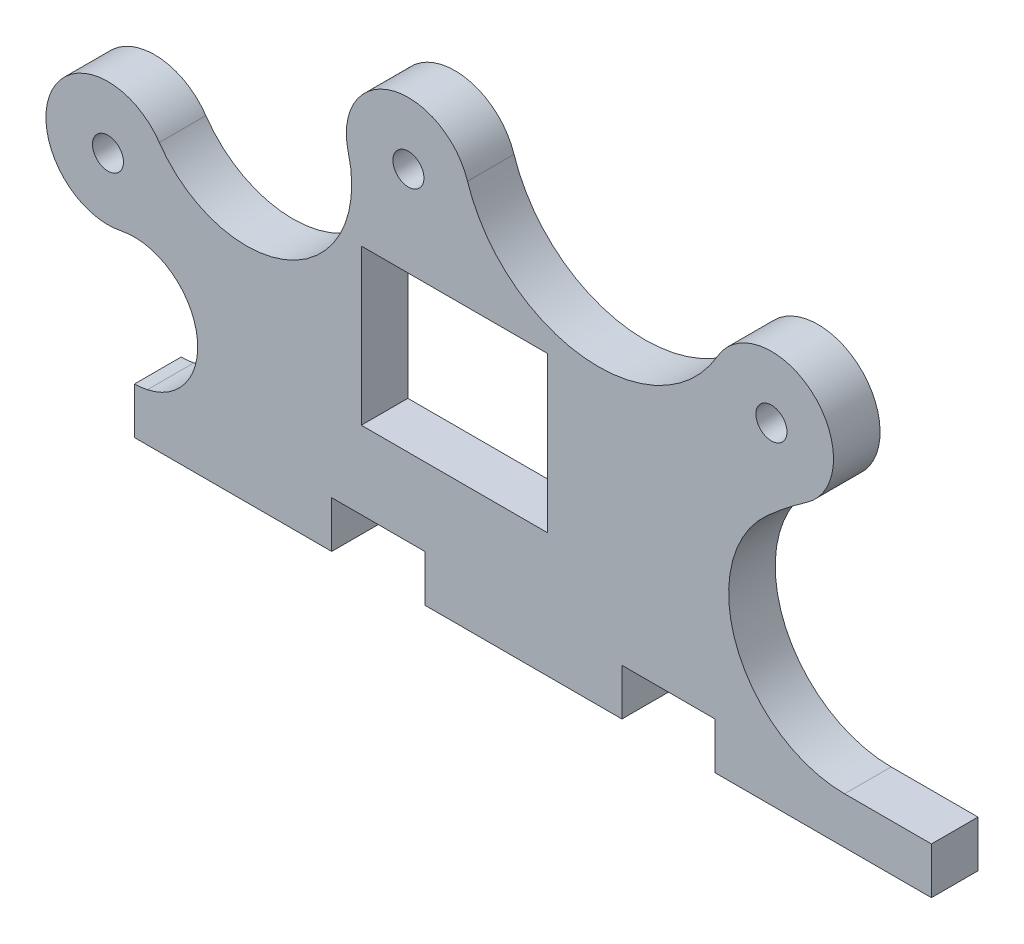
SolidWorks part; units mm, degrees
material "Acrylic (Medium-high impact)"
ref_plane "Front Plane" through (0, 0, 0) normal (0, 0, 1) x (1, 0, 0)
ref_plane "Top Plane" through (0, 0, 0) normal (0, 1, 0) x (1, 0, 0)
ref_plane "Right Plane" through (0, 0, 0) normal (1, 0, 0) x (0, 0, -1)
sketch "스케치2" plane through (0, 0, 0) normal (0, 0, 1) x (1, 0, 0)
  line L0 (-17.4812, 10.16) -> (-17.4856, 10.1652) construction
  line L1 (-17.4812, -10.16) -> (17.4812, -10.16) construction
  line L2 (-17.4812, -10.16) -> (-17.4812, 10.16) construction
  line L3 (-17.4812, 10.16) -> (17.4812, 10.16) construction
  line L4 (17.4812, -10.16) -> (17.4812, 10.16) construction
  line L5 (-17.4812, -10.16) -> (17.4812, 10.16) construction
  line L6 (-17.4812, 10.16) -> (17.4812, -10.16) construction
  line L7 (-17.4856, 10.1652) -> (-15.1875, 12.0936) construction
  line L8 (-15.1875, 12.0936) -> (-13.565, 10.16) construction
  line L9 (-0.865, 10.16) -> (-0.865, 19.05) construction
  line L10 (-0.865, 19.05) -> (2.135, 19.05) construction
  line L11 (2.135, 19.05) -> (2.135, 10.16) construction
  line L12 (13.565, 10.16) -> (20.4918, 18.415) construction
  line L13 (20.4918, 18.415) -> (22.7899, 16.4866) construction
  line L14 (22.7899, 16.4866) -> (17.4812, 10.16) construction
  line L16 (-13.565, 10.16) -> (-0.865, 10.16) construction
  line L17 (2.135, 10.16) -> (13.565, 10.16) construction
  line L18 (-2.3992, 6.954) -> (9.6008, 6.954)
  line L19 (-2.3992, 6.954) -> (-2.3992, 16.954)
  line L20 (9.6008, 6.954) -> (9.6008, 16.954)
  line L21 (-2.3992, 16.954) -> (9.6008, 16.954)
  line L22 (-2.3992, 6.954) -> (9.6008, 16.954) construction
  line L23 (9.6008, 6.954) -> (-2.3992, 16.954) construction
  line L24 (-25.4856, -6.7583) -> (31.5012, -6.7583)
  circle A0 centre (-18.7201, 13.97) radius 4 construction
  circle A1 centre (0.635, 22.7581) radius 4 construction
  circle A2 centre (24.0244, 20.2914) radius 4 construction
  circle A3 centre (-18.7201, 13.97) radius 1
  circle A4 centre (0.635, 22.7581) radius 1
  circle A5 centre (24.0244, 20.2914) radius 1
  arc A6 (-17.4856, 10.1652) -> (-15.1875, 12.0936) centre (-18.7201, 13.97) cw construction
  arc A7 (-0.865, 19.05) -> (2.135, 19.05) centre (0.635, 22.7581) cw construction
  arc A8 (20.4918, 18.415) -> (22.7899, 16.4866) centre (24.0244, 20.2914) cw construction
  arc A9 (-22.9545, 18.415) -> (-10.6235, 16.7359) centre (-20.4631, -9.4067) cw
  arc A10 (-10.6235, 16.7359) -> (0.635, 27.7632) centre (13.3905, 3.4795) cw
  arc A11 (0.635, 27.7632) -> (12.5325, 20.99) centre (-6.5484, 1.3094) cw
  arc A12 (12.5325, 20.99) -> (26.8856, 25.7756) centre (25.0332, 7.4143) cw
  arc A13 (26.8856, 25.7756) -> (27.9802, 4.2635) centre (9.9466, 14.1299) cw
  arc A14 (-22.9545, 18.415) -> (-25.3331, 6.954) centre (4.2395, 6.7937) ccw
  arc A15 (27.9802, 4.2635) -> (41.6305, 2.763) centre (32.6157, -16.4059) cw
  arc A16 (41.6305, 2.763) -> (31.5012, -6.7583) centre (31.5012, 3.3904) cw
  arc A17 (-25.3331, 6.954) -> (-37.8665, 3.5862) centre (-28.6886, -5.5641) ccw
  arc A18 (-37.8665, 3.5862) -> (-25.4856, -6.7583) centre (-25.4856, 5.8231) ccw
  point P0 (0, 0)
  point P31 (3.6008, 11.954)
  dimension "D3" = 3
  dimension "D4" = 2
  dimension "D5" = 12.7
  dimension "D2" = 20.32
  dimension "D6" = 11.43
  dimension "D7" = 3
  dimension "D8" = 130
  dimension "D9" = 3.81
  dimension "D10" = 50
  dimension "D11" = 8.89
  dimension "D12" = 8.255
  dimension "D14" = 12
  dimension "D15" = 10
  dimension "D16" = 21.082
extrude "보스-돌출1" add sketch "스케치2" along normal blind 3
sketch "스케치3" plane through (0, 0, 3) normal (0, 0, 1) x (1, 0, 0)
  line L0 (-25.4856, -6.7583) -> (31.5012, -6.7583) construction
  line L1 (-33.1668, -20.0933) -> (34.3332, -20.0933)
  line L2 (-33.1668, -20.0933) -> (-33.1668, -1.0433)
  line L3 (-33.1668, -1.0433) -> (34.3332, -1.0433)
  line L4 (34.3332, -20.0933) -> (34.3332, -1.0433)
  line L5 (-33.1668, -20.0933) -> (34.3332, -1.0433) construction
  line L6 (-33.1668, -1.0433) -> (34.3332, -20.0933) construction
  point P0 (0.5832, -10.5683)
  dimension "D1" = 67.5
  dimension "D2" = 19.05
  dimension "D3" = 3.81
extrude "컷-돌출1" cut sketch "스케치3" against normal up to surface (3 mm away) up to face at (25.0244, 20.2914, 0)
sketch "스케치4" plane through (0, 0, 3) normal (0, 0, 1) x (1, 0, 0)
  line L1 (-33.1668, -1.0433) -> (34.3332, -1.0433) construction
  line L2 (-33.1668, -1.0433) -> (-33.1668, 1.9567) construction
  line L3 (-33.1668, 1.9567) -> (34.3332, 1.9567) construction
  line L4 (34.3332, -1.0433) -> (34.3332, 1.9567) construction
  line L5 (-33.1668, -1.0433) -> (34.3332, 1.9567) construction
  line L6 (-33.1668, 1.9567) -> (34.3332, -1.0433) construction
  line L7 (-23.0068, 1.9567) -> (-17.0068, 1.9567)
  line L8 (-23.0068, 1.9567) -> (-23.0068, -1.0433)
  line L9 (-23.0068, -1.0433) -> (-17.0068, -1.0433)
  line L10 (-17.0068, 1.9567) -> (-17.0068, -1.0433)
  line L11 (-23.0068, 1.9567) -> (-17.0068, -1.0433) construction
  line L12 (-23.0068, -1.0433) -> (-17.0068, 1.9567) construction
  line L13 (14.3932, 1.9567) -> (20.3932, 1.9567)
  line L14 (14.3932, 1.9567) -> (14.3932, -1.0433)
  line L15 (14.3932, -1.0433) -> (20.3932, -1.0433)
  line L16 (20.3932, 1.9567) -> (20.3932, -1.0433)
  line L17 (14.3932, 1.9567) -> (20.3932, -1.0433) construction
  line L18 (14.3932, -1.0433) -> (20.3932, 1.9567) construction
  line L19 (-4.3068, -1.0433) -> (1.6932, -1.0433)
  line L20 (-4.3068, -1.0433) -> (-4.3068, 1.9567)
  line L21 (-4.3068, 1.9567) -> (1.6932, 1.9567)
  line L22 (1.6932, -1.0433) -> (1.6932, 1.9567)
  line L23 (-4.3068, -1.0433) -> (1.6932, 1.9567) construction
  line L24 (-4.3068, 1.9567) -> (1.6932, -1.0433) construction
  point P4 (0.5832, 0.4567)
  point P5 (-23.0068, 0.4567)
  point P12 (-20.0068, 0.4567)
  point P18 (17.3932, 0.4567)
  point P22 (-1.3068, 0.4567)
  point P23 (-4.3068, 0.4567)
  point P24 (14.3932, 0.4567)
  dimension "D1" = 3
  dimension "D2" = 6
  dimension "D3" = 6
  dimension "D4" = 6
  dimension "D5" = 10.16
  dimension "D6" = 12.7
  dimension "D7" = 12.7
extrude "컷-돌출2" cut sketch "스케치4" against normal up to surface (3 mm away) up to face at (1.33, 9.2291, 0)
sketch "스케치6" plane through (0, 0, 3) normal (0, 0, 1) x (1, 0, 0)
  line L2 (-30.4176, 1.9567) -> (-23.0068, 1.9567) construction
  line L3 (-23.0068, 1.9567) -> (-23.0068, -1.0433) construction
  line L4 (-17.0068, 1.9567) -> (-23.0068, 1.9567)
  line L5 (28.7361, 1.9567) -> (34.3332, 1.9567)
  line L6 (34.3332, 1.9567) -> (34.3332, -1.0433)
  line L7 (28.7361, 1.9567) -> (20.3932, 1.9567) construction
  line L8 (-23.0068, -1.0433) -> (-33.1668, -1.0433) construction
  line L9 (-23.0068, -1.0433) -> (-33.1668, -1.0433)
  line L10 (-23.0068, 1.9567) -> (-23.0068, -1.0433)
  line L11 (-17.0068, 1.9567) -> (-23.0068, 1.9567) construction
  line L12 (-17.0068, -1.0433) -> (-17.0068, 1.9567) construction
  line L15 (-23.0068, -1.0433) -> (-23.0068, 1.9567)
  line L16 (-23.0068, 1.9567) -> (-17.0068, 1.9567)
  line L17 (-17.0068, 1.9567) -> (-17.0068, -1.0433)
  line L18 (-17.0068, -1.0433) -> (-4.3068, -1.0433)
  line L19 (-4.3068, -1.0433) -> (-4.3068, 1.9567)
  line L20 (-4.3068, 1.9567) -> (1.6932, 1.9567)
  line L21 (1.6932, 1.9567) -> (1.6932, -1.0433)
  line L22 (1.6932, -1.0433) -> (14.3932, -1.0433)
  line L23 (14.3932, -1.0433) -> (14.3932, 1.9567)
  line L24 (14.3932, 1.9567) -> (20.3932, 1.9567)
  line L25 (20.3932, 1.9567) -> (20.3932, -1.0433)
  line L26 (20.3932, -1.0433) -> (34.3332, -1.0433)
  line L27 (34.3332, -1.0433) -> (34.3332, -6.3552)
  line L28 (-33.1668, -4.1413) -> (-33.1668, -1.0433)
  line L29 (-33.1668, -1.0433) -> (-23.0068, -1.0433)
  line L42 (34.3332, -1.0433) -> (34.3332, -6.3552)
  line L43 (-33.1668, -4.1413) -> (-33.1668, -1.0433)
  circle A0 centre (-18.7201, 13.97) radius 4 construction
  arc A1 (-15.4147, 16.2227) -> (-22.5306, 12.7536) centre (-18.7201, 13.97) ccw
  circle A2 centre (0.635, 22.7581) radius 4 construction
  arc A3 (4.4403, 23.9909) -> (-3.2365, 21.7522) centre (0.635, 22.7581) ccw
  circle A4 centre (24.0244, 20.2914) radius 4 construction
  arc A5 (26.3054, 17.0056) -> (20.56, 22.2909) centre (24.0244, 20.2914) ccw
  arc A6 (-15.4147, 16.2227) -> (-3.2365, 21.7522) centre (-9.8059, 20.0454) ccw
  arc A12 (12.5325, 20.99) -> (0.635, 27.7632) centre (-6.5484, 1.3094) ccw construction
  arc A13 (26.8856, 25.7756) -> (12.5325, 20.99) centre (25.0332, 7.4143) ccw construction
  arc A14 (12.5325, 20.99) -> (0.635, 27.7632) centre (-6.5484, 1.3094) ccw
  arc A15 (26.8856, 25.7756) -> (12.5325, 20.99) centre (25.0332, 7.4143) ccw
  arc A16 (26.3054, 17.0056) -> (23.7498, 14.9852) centre (41.2708, -4.5517) ccw
  arc A17 (23.7498, 14.9852) -> (28.7361, 1.9567) centre (28.7361, 9.4252) ccw
  arc A19 (4.4403, 23.9909) -> (20.56, 22.2909) centre (12.8781, 26.7246) ccw
  arc A20 (34.3332, -6.3552) -> (41.6305, 2.763) centre (31.5012, 3.3904) ccw
  arc A21 (41.6305, 2.763) -> (27.9802, 4.2635) centre (32.6157, -16.4059) ccw
  arc A22 (27.9802, 4.2635) -> (26.8856, 25.7756) centre (9.9466, 14.1299) ccw
  arc A23 (26.8856, 25.7756) -> (12.5325, 20.99) centre (25.0332, 7.4143) ccw
  arc A24 (12.5325, 20.99) -> (0.635, 27.7632) centre (-6.5484, 1.3094) ccw
  arc A25 (0.635, 27.7632) -> (-10.6235, 16.7359) centre (13.3905, 3.4795) ccw
  arc A26 (-10.6235, 16.7359) -> (-22.9545, 18.415) centre (-20.4631, -9.4067) ccw
  arc A27 (-22.9545, 18.415) -> (-25.3331, 6.954) centre (4.2395, 6.7937) ccw
  arc A28 (-25.3331, 6.954) -> (-37.8665, 3.5862) centre (-28.6886, -5.5641) ccw
  arc A29 (-37.8665, 3.5862) -> (-33.1668, -4.1413) centre (-25.4856, 5.8231) ccw
  arc A30 (34.3332, -6.3552) -> (41.6305, 2.763) centre (31.5012, 3.3904) ccw
  arc A31 (41.6305, 2.763) -> (27.9802, 4.2635) centre (32.6157, -16.4059) ccw
  arc A32 (27.9802, 4.2635) -> (26.8856, 25.7756) centre (9.9466, 14.1299) ccw
  arc A35 (0.635, 27.7632) -> (-10.6235, 16.7359) centre (13.3905, 3.4795) ccw
  arc A36 (-10.6235, 16.7359) -> (-22.9545, 18.415) centre (-20.4631, -9.4067) ccw
  arc A37 (-22.9545, 18.415) -> (-25.3331, 6.954) centre (4.2395, 6.7937) ccw
  arc A38 (-25.3331, 6.954) -> (-37.8665, 3.5862) centre (-28.6886, -5.5641) ccw
  arc A39 (-37.8665, 3.5862) -> (-33.1668, -4.1413) centre (-25.4856, 5.8231) ccw
  arc A42 (-22.5306, 12.7536) -> (-17.8882, 10.0575) centre (-18.7201, 13.97) ccw
  arc A46 (-16.1843, 2.0432) -> (-17.8882, 10.0575) centre (-17.0362, 6.0503) ccw
  arc A47 (-17.0068, 1.9567) -> (-16.1843, 2.0432) centre (-17.0068, 5.9119) ccw
  dimension "D1" = 0
extrude "컷-돌출3" cut sketch "스케치6" against normal up to surface (3 mm away) up to face at (0.0643, 5.0184, 0)
